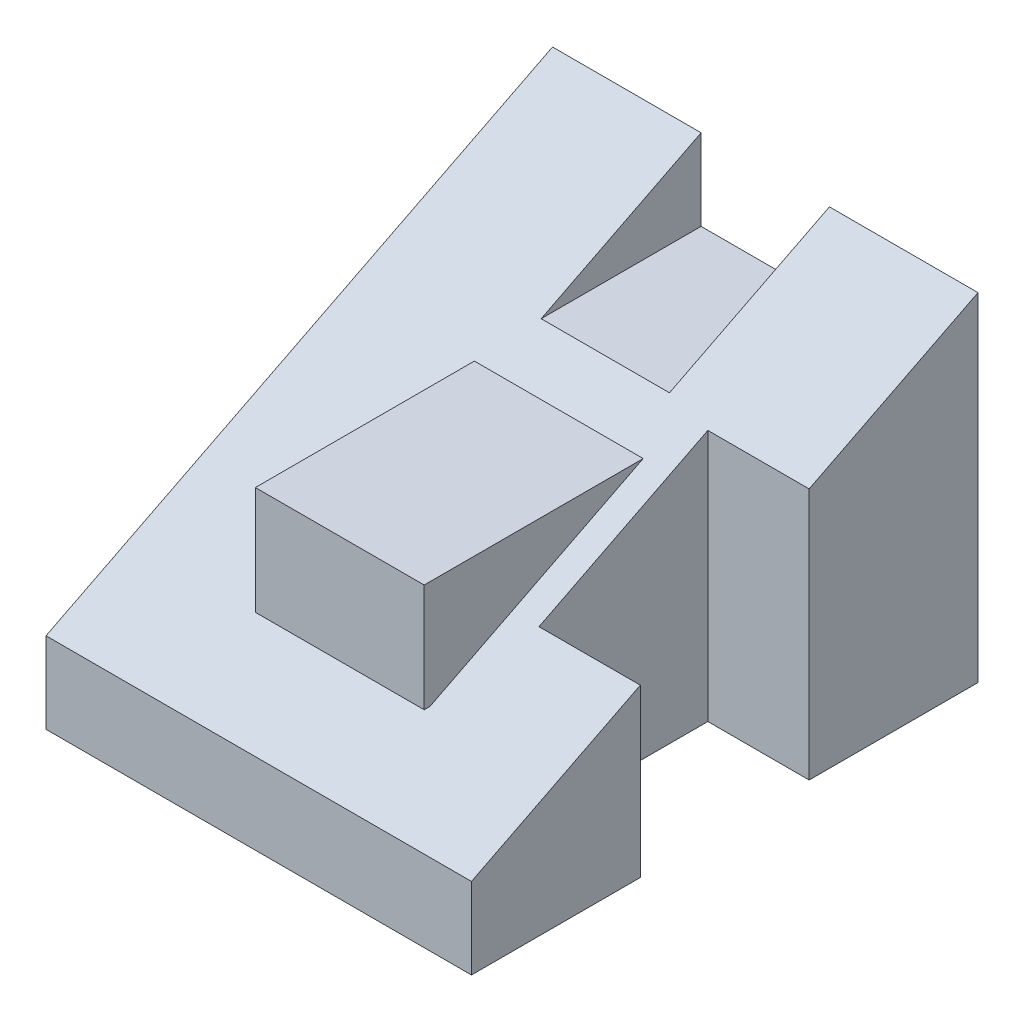
SolidWorks part; units mm, degrees
ref_plane "Front Plane" through (0, 0, 0) normal (0, 0, 1) x (1, 0, 0)
ref_plane "Top Plane" through (0, 0, 0) normal (0, 1, 0) x (1, 0, 0)
ref_plane "Right Plane" through (0, 0, 0) normal (1, 0, 0) x (0, 0, -1)
sketch "Sketch1" plane through (0, 0, 0) normal (1, 0, 0) x (0, 0, -1)
  line L0 (0, 0) -> (75, 0)
  line L1 (75, 0) -> (75, 50)
  line L2 (75, 50) -> (0, 12)
  line L3 (0, 12) -> (0, 0)
  dimension "D1" = 12
  dimension "D2" = 75
  dimension "D3" = 50
extrude "Boss-Extrude1" add sketch "Sketch1" against normal blind 63
sketch "Sketch2" plane through (0, 0, 0) normal (1, 0, 0) x (0, 0, -1)
  line L0 (25, 24.6667) -> (25, 0)
  line L1 (75, 50) -> (0, 12) construction
  line L2 (0, 0) -> (75, 0) construction
  line L3 (50, 37.3333) -> (50, 0)
  line L4 (0, 12) -> (0, 0) construction
  line L5 (75, 0) -> (75, 50) construction
  line L6 (25, 24.6667) -> (50, 37.3333)
  line L7 (25, 0) -> (50, 0)
  point P10 (0, 6)
  dimension "D1" = 25
  dimension "D2" = 25
extrude "Cut-Extrude1" cut sketch "Sketch2" against normal blind 15
sketch "Sketch3" plane through (0, 0, -75) normal (0, 0, -1) x (-1, 0, 0)
  line L0 (22, 50) -> (22, 38)
  line L1 (63, 50) -> (0, 50) construction
  line L2 (22, 38) -> (41, 38)
  line L3 (41, 38) -> (41, 50)
  line L4 (41, 50) -> (22, 50)
  line L5 (0, 0) -> (0, 50) construction
  line L6 (63, 0) -> (63, 50) construction
  dimension "D1" = 22
  dimension "D2" = 22
  dimension "D3" = 12
extrude "Cut-Extrude2" cut sketch "Sketch3" against normal up to next
sketch "Sketch4" plane through (0, 0, 0) normal (0, 0, 1) x (1, 0, 0)
  line L0 (-63, 50) -> (-63, 12) construction
  line L1 (-44, 34.5104) -> (-19, 34.5104)
  line L2 (-44, 34.5104) -> (-44, 18.5104)
  line L3 (-44, 18.5104) -> (-19, 18.5104)
  line L4 (-19, 34.5104) -> (-19, 18.5104)
  line L5 (-44, 34.5104) -> (-19, 18.5104) construction
  line L6 (-44, 18.5104) -> (-19, 34.5104) construction
  point P0 (-31.5, 26.5104)
  point P5 (-33.9676, 28.8776)
  point P8 (0, 0)
  point P9 (-44, 20.7195)
  point P10 (-44, 34.0142)
  point P11 (-44, 34.82)
  point P12 (-44, 34.7193)
  point P13 (-19, 34.7633)
  point P14 (-19, 31.6599)
  point P15 (-19, 34.0823)
  point P16 (-19, 21.6767)
  point P17 (-19, 19.4173)
  point P18 (0, 0)
  point P19 (-19, 37.4437)
  point P20 (-19, 35.3197)
  point P21 (-19, 22.9198)
  point P22 (-19, 36.0146)
  point P23 (-19, 34.0112)
  point P24 (-19, 34.5104)
  dimension "D1" = 19
  dimension "D2" = 25
  dimension "D3" = 16
extrude "Boss-Extrude2" add sketch "Sketch4" against normal up to next from offset 12 contours L4 L1 L2 L3
